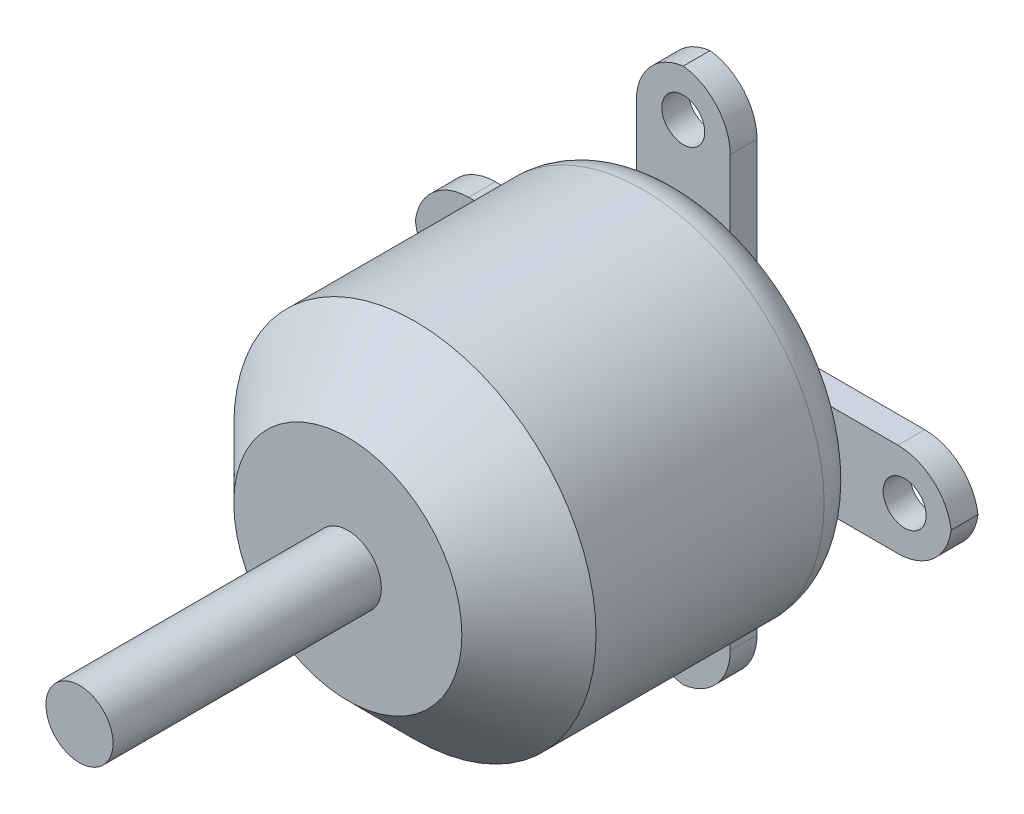
SolidWorks part; units mm, degrees
ref_plane "Front Plane" through (0, 0, 0) normal (0, 0, 1) x (1, 0, 0)
ref_plane "Top Plane" through (0, 0, 0) normal (0, 1, 0) x (1, 0, 0)
ref_plane "Right Plane" through (0, 0, 0) normal (1, 0, 0) x (0, 0, -1)
sketch "Sketch1" plane through (0, 0, 0) normal (0, 0, 1) x (1, 0, 0)
  circle A0 centre (0, 0) radius 13.5
extrude "Boss-Extrude1" add sketch "Sketch1" along normal blind 25
sketch "Sketch2" plane through (0, 0, 25) normal (0, 0, 1) x (1, 0, 0)
  circle A0 centre (0, 0) radius 2.5
extrude "Boss-Extrude2" add sketch "Sketch2" along normal blind 20
fillet "Fillet1" radius 3 1 edges at (13.5, 0, 0)
chamfer "Chamfer1" distance 5 angle 45 1 edges at (13.5, 0, 25)
sketch "Sketch3" plane through (0, 0, 0) normal (0, 0, -1) x (-1, 0, 0)
  line L0 (-3.5, -7.5) -> (-3.5, -16)
  line L1 (-16, 3.5) -> (-7.5, 3.5)
  line L3 (-16, -3.5) -> (-7.5, -3.5)
  line L6 (-3.5, 16) -> (-3.5, 7.5)
  line L8 (3.5, 16) -> (3.5, 7.5)
  line L9 (3.5, -7.5) -> (3.5, -16)
  line L10 (7.5, 3.5) -> (16, 3.5)
  line L11 (7.5, -3.5) -> (16, -3.5)
  arc A0 (3.5, 7.5) -> (7.5, 3.5) centre (7.5, 7.5) ccw
  arc A1 (3.5, -7.5) -> (7.5, -3.5) centre (7.5, -7.5) cw
  arc A2 (-3.5, -7.5) -> (-7.5, -3.5) centre (-7.5, -7.5) ccw
  arc A3 (-3.5, 7.5) -> (-7.5, 3.5) centre (-7.5, 7.5) cw
  circle A4 centre (-16.5, 0) radius 1.6
  arc A5 (-3.5, -16) -> (0, -19.9686) centre (0.5, -16) ccw
  arc A6 (0, -19.9686) -> (3.5, -16) centre (-0.5, -16) ccw
  arc A7 (16, -3.5) -> (19.9686, 0) centre (16, 0.5) ccw
  arc A8 (16, 3.5) -> (19.9686, 0) centre (16, -0.5) cw
  arc A9 (0, 19.9686) -> (3.5, 16) centre (-0.5, 16) cw
  arc A10 (0, 19.9686) -> (-3.5, 16) centre (0.5, 16) ccw
  arc A11 (-16, 3.5) -> (-19.9686, 0) centre (-16, -0.5) ccw
  arc A12 (-19.9686, 0) -> (-16, -3.5) centre (-16, 0.5) ccw
  circle A13 centre (0, 16.5) radius 1.6
  circle A14 centre (16.5, 0) radius 1.6
  circle A15 centre (0, -16.5) radius 1.6
  point P15 (3.5, 3.5)
  point P18 (3.5, -3.5)
  point P29 (3.5, -20)
  point P32 (20, -3.5)
  point P37 (3.5, 20)
  point P40 (-3.5, 20)
  point P43 (-20, 3.5)
  point P46 (-20, -3.5)
  point P56 (0, 0)
  dimension "D9" = 4
  dimension "D10" = 16.5
  dimension "D11" = 4
  dimension "D1" = 7
  dimension "D2" = 7
  dimension "D3" = 3.5
  dimension "D4" = 3.5
  dimension "D5" = 40
  dimension "D8" = 40
  dimension "D12" = 4
extrude "Boss-Extrude3" add sketch "Sketch3" along normal blind 2
sketch "Sketch4" plane through (0, 0, -2) normal (0, 0, -1) x (-1, 0, 0)
  circle A0 centre (0, 0) radius 4
extrude "Cut-Extrude1" cut sketch "Sketch4" against normal blind 2
